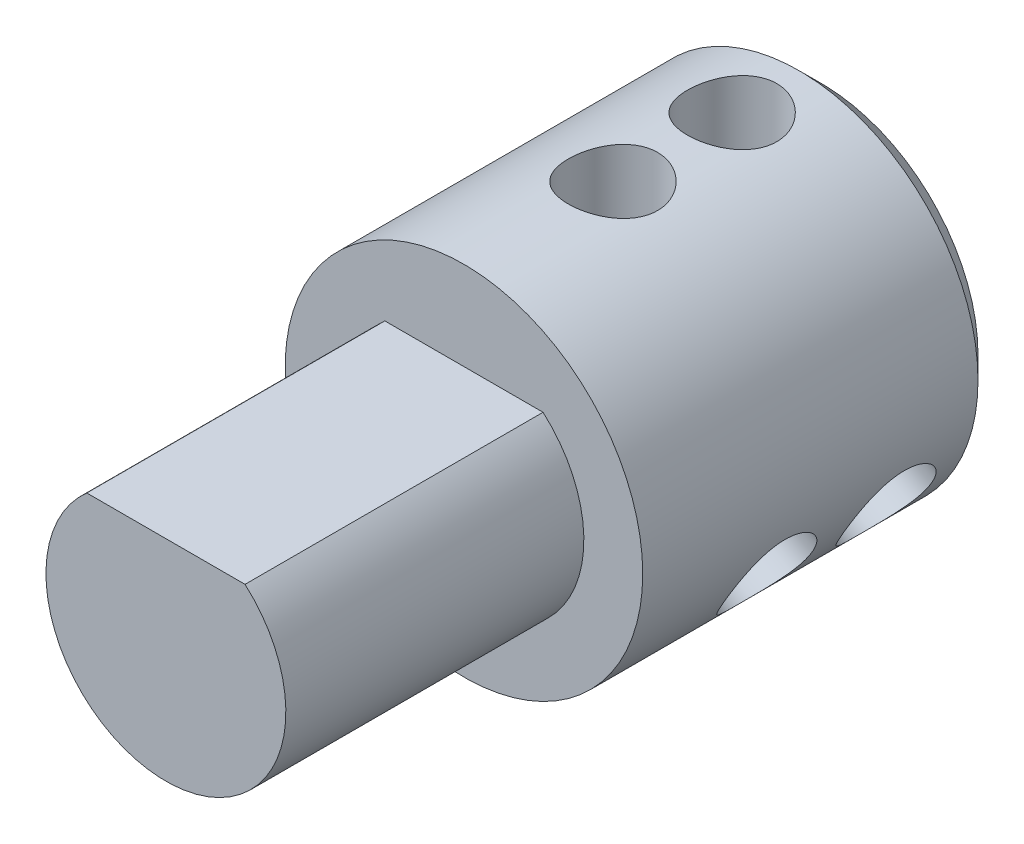
SolidWorks part; units mm, degrees
ref_plane "Front" through (0, 0, 0) normal (0, 0, 1) x (1, 0, 0)
ref_plane "Top" through (0, 0, 0) normal (0, 1, 0) x (1, 0, 0)
ref_plane "Right" through (0, 0, 0) normal (1, 0, 0) x (0, 0, -1)
sketch "Sketch1" plane through (0, 0, 0) normal (0, 0, 1) x (1, 0, 0)
  line L0 (-1.5984, 1.475) -> (1.5984, 1.475)
  line L1 (0, 0) -> (0, 1.475) construction
  line L2 (0, 1.475) -> (0, 2.175) construction
  circle A0 centre (0, 0) radius 2.175
  circle A1 centre (0, 0) radius 6
  point P6 (0, -2.175)
  dimension "D1" = 4.35
  dimension "D3" = 12
  dimension "D2" = 3.65
extrude "Boss-Extrude1" add sketch "Sketch1" along normal blind 10 contours A1 A0 | L0 A0
sketch "Sketch3" plane through (0, 0, 0) normal (0, 1, 0) x (1, 0, 0)
  circle A0 centre (0, -3) radius 1.5
  circle A2 centre (0, -7) radius 1.5
  point P5 (0, 0)
  dimension "D1" = 3
  dimension "D2" = 3
  dimension "D3" = 4
extrude "Cut-Extrude1" cut sketch "Sketch3" along normal up to next
sketch "Sketch4" plane through (0, 0, 10) normal (0, 0, 1) x (1, 0, 0)
  circle A0 centre (0, 0) radius 6
  circle A1 centre (0, 0) radius 6 construction
extrude "Boss-Extrude2" add sketch "Sketch4" along normal blind 2
sketch "Sketch6" plane through (0, 0, 12) normal (0, 0, 1) x (1, 0, 0)
  line L0 (-2.6552, 3.025) -> (2.6552, 3.025)
  circle A0 centre (0, 0) radius 4.025
  point P5 (0, -4.025)
  dimension "D1" = 8.05
  dimension "D2" = 7.05
extrude "Boss-Extrude3" add sketch "Sketch6" along normal blind 10 contours L0 A0
chamfer "Chamfer1" distance 0.75 angle 45 1 edges at (6, 0, 0)
pattern_circular "CirPattern1" count 3 over 360 of "Cut-Extrude1"
